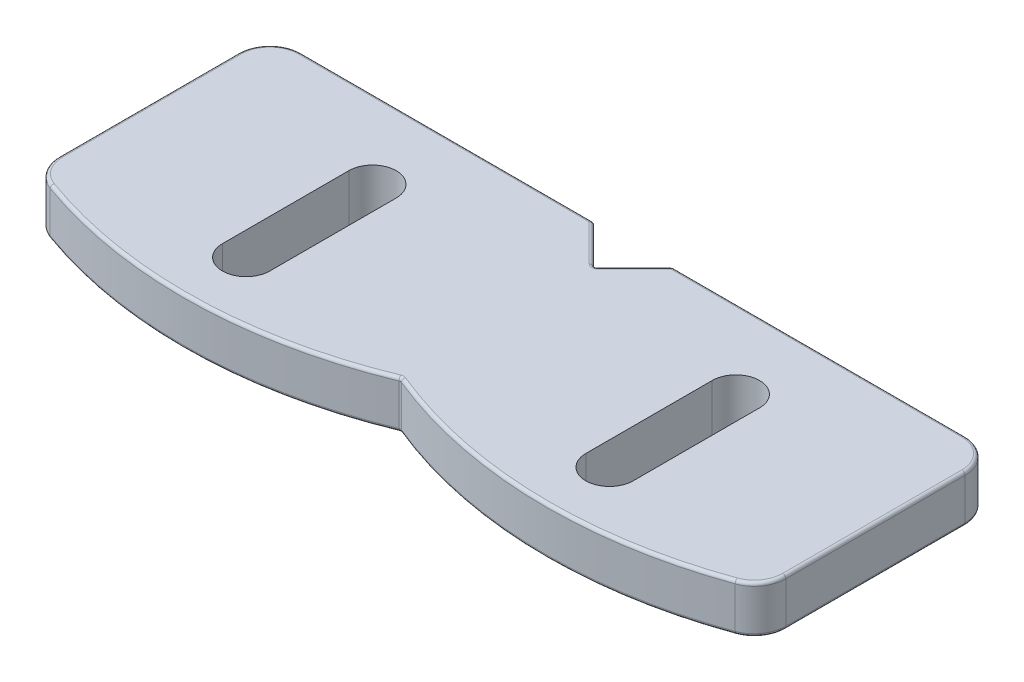
SolidWorks part; units mm, degrees
ref_plane "Front Plane" through (0, 0, 0) normal (0, 0, 1) x (1, 0, 0)
ref_plane "Top Plane" through (0, 0, 0) normal (0, 1, 0) x (1, 0, 0)
ref_plane "Right Plane" through (0, 0, 0) normal (1, 0, 0) x (0, 0, -1)
sketch "Sketch1" plane through (0, 0, 0) normal (0, 1, 0) x (1, 0, 0)
  line L0 (0, 0) -> (0, 17) construction
  line L1 (-2.5, 17) -> (-21, 17)
  line L2 (-23, 15) -> (-23, 3.6609)
  line L3 (-23, 0) -> (0, 0) construction
  line L4 (-11.5, 12) -> (-11.5, 4) construction
  line L5 (-10, 12) -> (-10, 4)
  line L6 (-13, 12) -> (-13, 4)
  line L7 (-2.5, 17) -> (0, 14.5)
  line L8 (2.5, 17) -> (0, 14.5)
  line L9 (23, 15) -> (23, 3.6609)
  line L10 (2.5, 17) -> (21, 17)
  line L11 (11.5, 12) -> (11.5, 4) construction
  line L12 (10, 12) -> (10, 4)
  line L13 (13, 12) -> (13, 4)
  arc A0 (-10, 12) -> (-13, 12) centre (-11.5, 12) ccw
  arc A1 (-13, 4) -> (-10, 4) centre (-11.5, 4) ccw
  arc A2 (-21.6786, 1.7795) -> (0, 2.2917) centre (-11.5, 30) ccw
  arc A3 (-21.6786, 1.7795) -> (-23, 3.6609) centre (-21, 3.6609) cw
  arc A4 (-21, 17) -> (-23, 15) centre (-21, 15) ccw
  arc A5 (21.6786, 1.7795) -> (0, 2.2917) centre (11.5, 30) cw
  arc A6 (21, 17) -> (23, 15) centre (21, 15) cw
  arc A7 (21.6786, 1.7795) -> (23, 3.6609) centre (21, 3.6609) ccw
  arc A8 (10, 12) -> (13, 12) centre (11.5, 12) cw
  arc A9 (13, 4) -> (10, 4) centre (11.5, 4) cw
  point P7 (-11.5, 8)
  point P31 (11.5, 8)
  dimension "D7" = 60
  dimension "D10" = 2
  dimension "D1" = 23
  dimension "D2" = 17
  dimension "D3" = 10
  dimension "D4" = 8
  dimension "D5" = 4
  dimension "D6" = 3
  dimension "D8" = 45
  dimension "D9" = 2.5
extrude "Boss-Extrude1" add sketch "Sketch1" along normal blind 3
ref_plane "Plane1" through (0, 0, -12) normal (0, 0, 1) x (0, -1, 0)
fillet "Fillet1" radius 0.2 28 edges at (11.75, 0, -17) (22.4142, 0, -16.4142) (23, 0, -9.3304) (22.6366, 0, -2.5113) (-11.75, 0, -17) (-22.4142, 0, -16.4142) (-23, 0, -9.3304) (-22.6366, 0, -2.5113) (11.75, 3, -17) (22.4142, 3, -16.4142) (23, 3, -9.3304) (22.6366, 3, -2.5113) (-11.75, 3, -17) (-22.4142, 3, -16.4142) (-23, 3, -9.3304) (-22.6366, 3, -2.5113) (0, 1.5, -2.2917) (-2.5, 1.5, -17) (2.5, 1.5, -17) (0, 1.5, -14.5) (1.25, 0, -15.75) (-1.25, 0, -15.75) (1.25, 3, -15.75) (-1.25, 3, -15.75) (10.7914, 0, -0.0084) (-10.7914, 0, -0.0084) (10.7914, 3, -0.0084) (-10.7914, 3, -0.0084)
